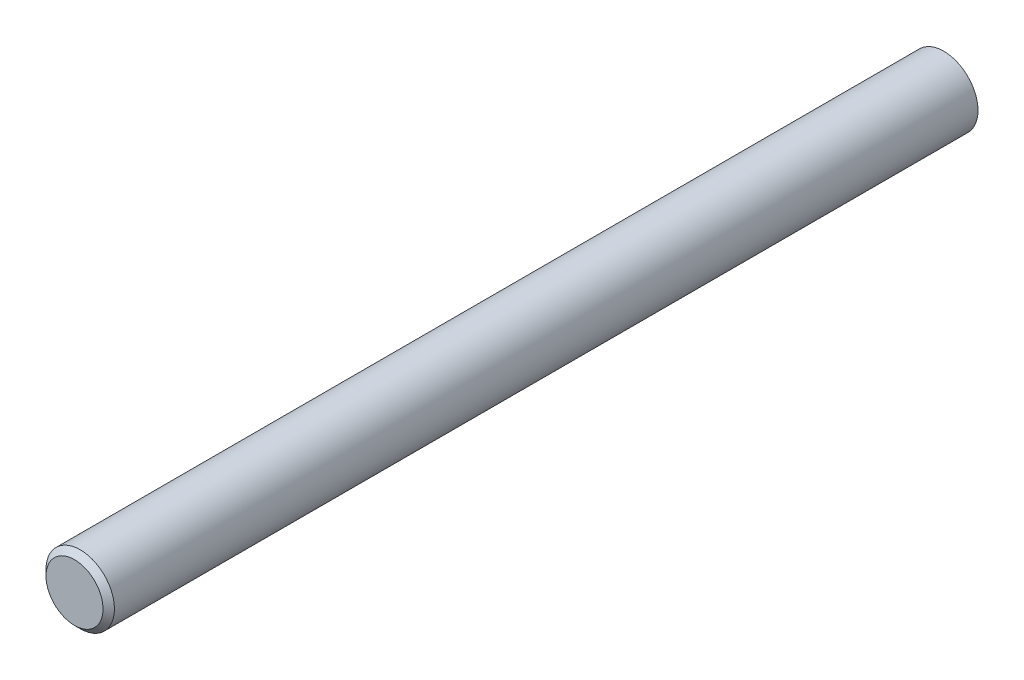
SolidWorks part; units mm, degrees
ref_plane "Ebene vorne" through (0, 0, 0) normal (0, 0, 1) x (1, 0, 0)
ref_plane "Ebene oben" through (0, 0, 0) normal (0, 1, 0) x (1, 0, 0)
ref_plane "Ebene rechts" through (0, 0, 0) normal (1, 0, 0) x (0, 0, -1)
sketch "Skizze1" plane through (0, 0, 0) normal (1, 0, 0) x (0, 0, -1)
  line L0 (7, 3) -> (2, 3) construction
  line L1 (54.2175, 3) -> (54.2175, 0) construction
  line L2 (0, 0) -> (99, 0) construction
  line L3 (7, 3) -> (54.2175, 3) construction
  line L4 (-22, 0) -> (0, 0) construction
  line L5 (-22, 3) -> (-22, 0) construction
  line L6 (2, 3) -> (-22, 3) construction
  line L7 (7, 3) -> (2, 3)
  line L8 (54.2175, 3) -> (54.2175, 0)
  line L9 (0, 0) -> (54.2175, 0)
  line L10 (7, 3) -> (54.2175, 3)
  line L11 (-22, 0) -> (0, 0)
  line L12 (-22, 3) -> (-22, 0)
  line L13 (2, 3) -> (-22, 3)
revolve "Rotation1" add sketch "Skizze1" angle 360 about L11
chamfer "Fase1" distance 0.5 angle 45 1 edges at (3, 0, 22)
